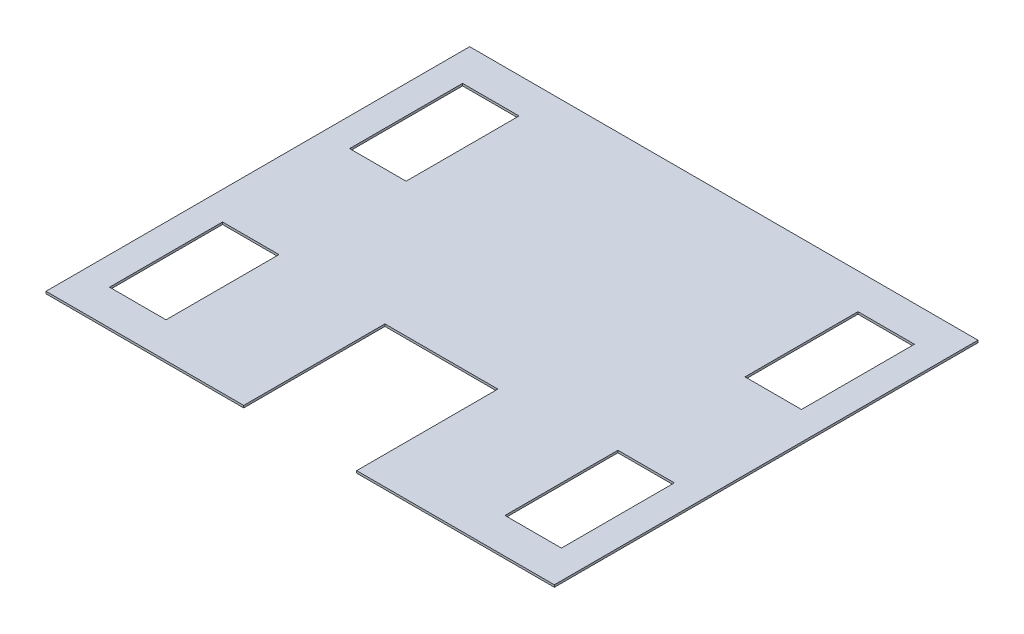
SolidWorks part; units mm, degrees
material "AISI 1035 Steel (SS)"
ref_plane "Front Plane" through (0, 0, 0) normal (0, 0, 1) x (1, 0, 0)
ref_plane "Top Plane" through (0, 0, 0) normal (0, 1, 0) x (1, 0, 0)
ref_plane "Right Plane" through (0, 0, 0) normal (1, 0, 0) x (0, 0, -1)
sketch "Sketch1" plane through (0, 0, 0) normal (0, 1, 0) x (1, 0, 0)
  line L1 (-228.6, 190.5) -> (228.6, 190.5)
  line L2 (-228.6, 190.5) -> (-228.6, -190.5)
  line L3 (-228.6, -190.5) -> (228.6, -190.5)
  line L4 (228.6, 190.5) -> (228.6, -190.5)
  line L5 (-228.6, 190.5) -> (228.6, -190.5) construction
  line L6 (-228.6, -190.5) -> (228.6, 190.5) construction
  point P0 (0, 0)
  dimension "D1" = 457.2
  dimension "D2" = 381
extrude "Boss-Extrude1" add sketch "Sketch1" along normal blind 2
sketch "Sketch119" plane through (0, 2, 0) normal (0, 1, 0) x (1, 0, 0)
  line L0 (-228.6, 190.5) -> (-152.4, 190.5)
  line L1 (228.6, 190.5) -> (-228.6, 190.5) construction
  line L2 (-152.4, 158.75) -> (-152.4, 57.15)
  line L3 (-152.4, 57.15) -> (-203.2, 57.15)
  line L4 (-203.2, 57.15) -> (-203.2, 158.75)
  line L5 (-203.2, 158.75) -> (-152.4, 158.75)
  line L6 (0, 190.5) -> (0, -213.0277) construction
  line L7 (-228.6, 0) -> (228.6, 0) construction
  line L8 (-228.6, 190.5) -> (-228.6, -190.5) construction
  line L9 (228.6, -190.5) -> (228.6, 190.5) construction
  line L10 (203.2, 158.75) -> (152.4, 158.75)
  line L11 (203.2, 57.15) -> (203.2, 158.75)
  line L12 (152.4, 57.15) -> (203.2, 57.15)
  line L13 (152.4, 158.75) -> (152.4, 57.15)
  line L14 (203.2, -57.15) -> (203.2, -158.75)
  line L15 (152.4, -57.15) -> (203.2, -57.15)
  line L16 (152.4, -158.75) -> (152.4, -57.15)
  line L17 (203.2, -158.75) -> (152.4, -158.75)
  line L18 (-203.2, -158.75) -> (-152.4, -158.75)
  line L19 (-203.2, -57.15) -> (-203.2, -158.75)
  line L20 (-152.4, -57.15) -> (-203.2, -57.15)
  line L21 (-152.4, -158.75) -> (-152.4, -57.15)
extrude "Cut-Extrude1" cut sketch "Sketch119" against normal through all contours L18 L21 L20 L19 | L2 L3 L4 L5 | L10 L13 L12 L11 | L14 L17 L16 L15
sketch "Sketch120" plane through (0, 2, 0) normal (0, 1, 0) x (1, 0, 0)
  line L1 (-228.6, -190.5) -> (228.6, -190.5) construction
  line L2 (-50.8, -190.5) -> (-50.8, -63.5)
  line L3 (-50.8, -63.5) -> (50.8, -63.5)
  line L4 (50.8, -63.5) -> (50.8, -190.5)
  line L5 (50.8, -190.5) -> (-50.8, -190.5)
extrude "Cut-Extrude2" cut sketch "Sketch120" against normal through all
